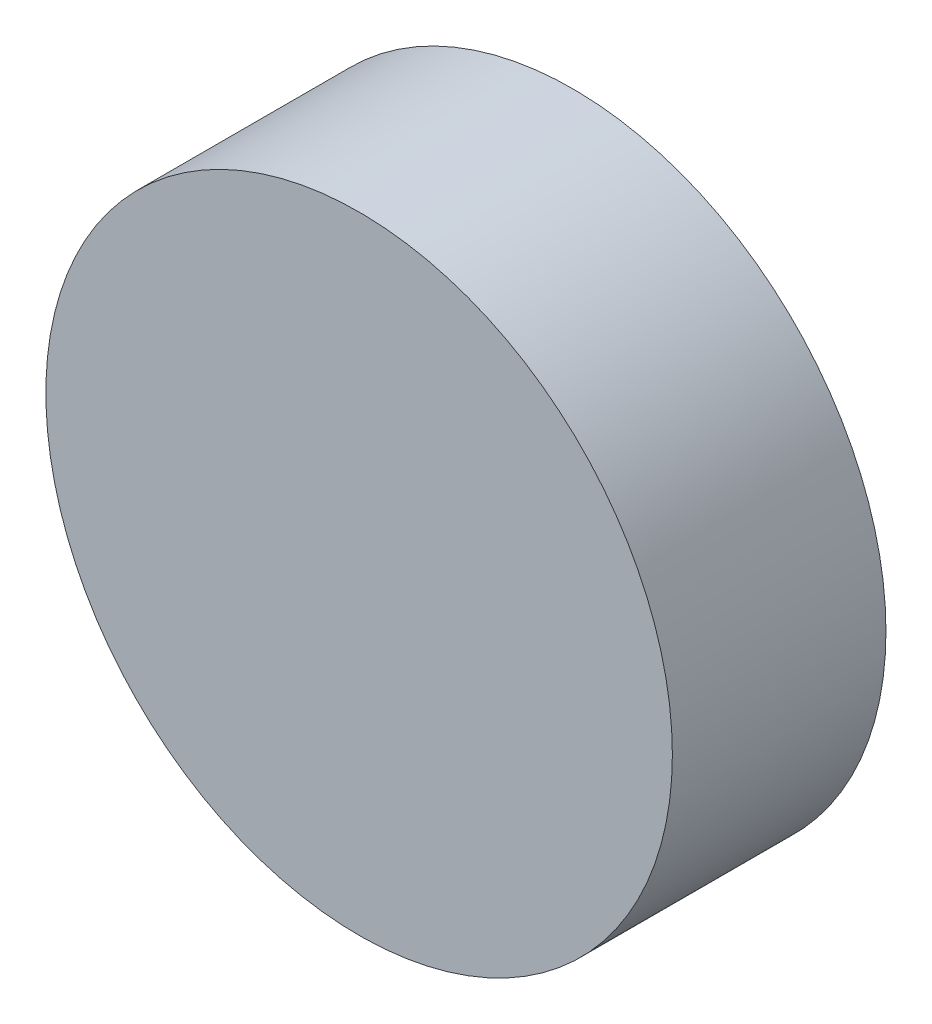
SolidWorks part; units mm, degrees
material "PE High Density"
ref_plane "Front" through (0, 0, 0) normal (0, 0, 1) x (1, 0, 0)
ref_plane "Top" through (0, 0, 0) normal (0, 1, 0) x (1, 0, 0)
ref_plane "Right" through (0, 0, 0) normal (1, 0, 0) x (0, 0, -1)
sketch "Sketch1" plane through (0, 0, 0) normal (0, 0, 1) x (1, 0, 0)
  circle A0 centre (0, 0) radius 22
extrude "Boss-Extrude1" add sketch "Sketch1" along normal blind 15
sketch "Sketch2" plane through (0, 0, 0) normal (0, 0, -1) x (-1, 0, 0)
  circle A0 centre (0, 0) radius 10
extrude "Cut-Extrude1" cut sketch "Sketch2" against normal blind 5
sketch "Sketch3" plane through (0, 0, 0) normal (0, 0, -1) x (-1, 0, 0)
  circle A0 centre (0, 0) radius 14.5931
  circle A1 centre (0, 0) radius 17.0758
extrude "Cut-Extrude2" cut sketch "Sketch3" against normal blind 8
